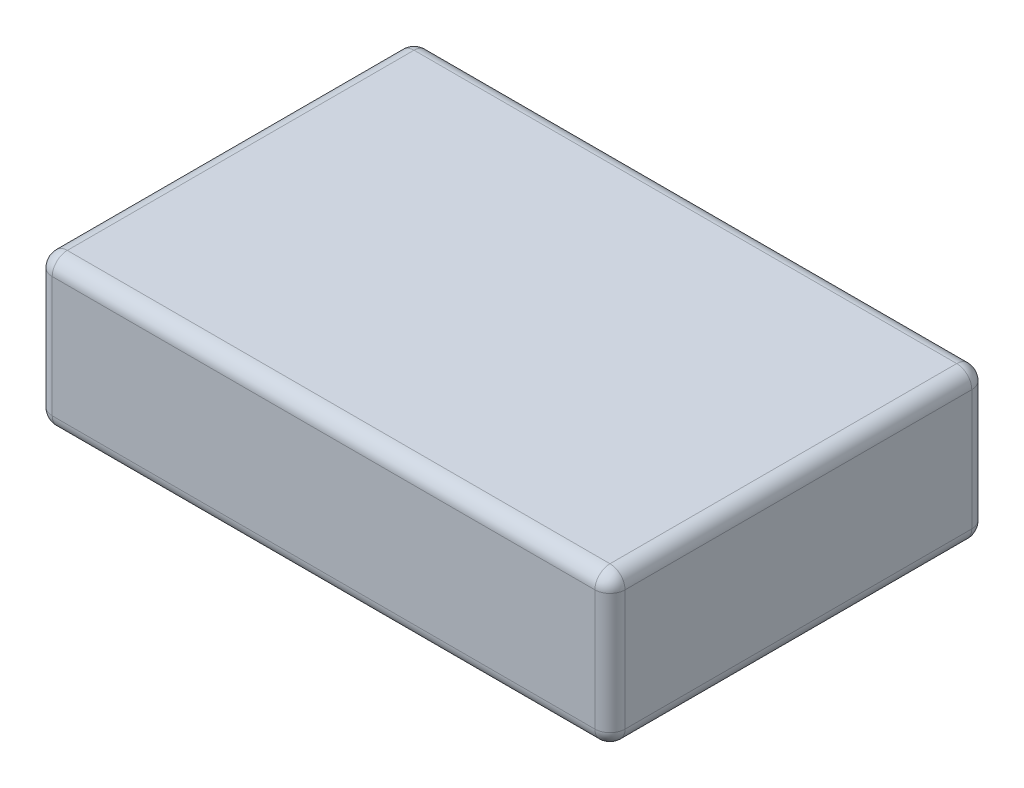
SolidWorks part; units mm, degrees
ref_plane "前视基准面" through (0, 0, 0) normal (0, 0, 1) x (1, 0, 0)
ref_plane "上视基准面" through (0, 0, 0) normal (0, 1, 0) x (1, 0, 0)
ref_plane "右视基准面" through (0, 0, 0) normal (1, 0, 0) x (0, 0, -1)
other "Configuration Table"
sketch "草图1" plane through (0, 0, 0) normal (0, 1, 0) x (1, 0, 0)
  line L1 (0, 0) -> (76, 0)
  line L2 (0, 0) -> (0, -50)
  line L3 (0, -50) -> (76, -50)
  line L4 (76, 0) -> (76, -50)
  dimension "D1" = 50
  dimension "D2" = 76
extrude "凸台-拉伸1" add sketch "草图1" along normal blind 20
fillet "圆角1" radius 2 12 edges at (0, 10, 0) (38, 0, 0) (0, 0, 25) (76, 10, 0) (76, 0, 25) (0, 10, 50) (76, 10, 50) (38, 0, 50) (38, 20, 0) (76, 20, 25) (38, 20, 50) (0, 20, 25)
